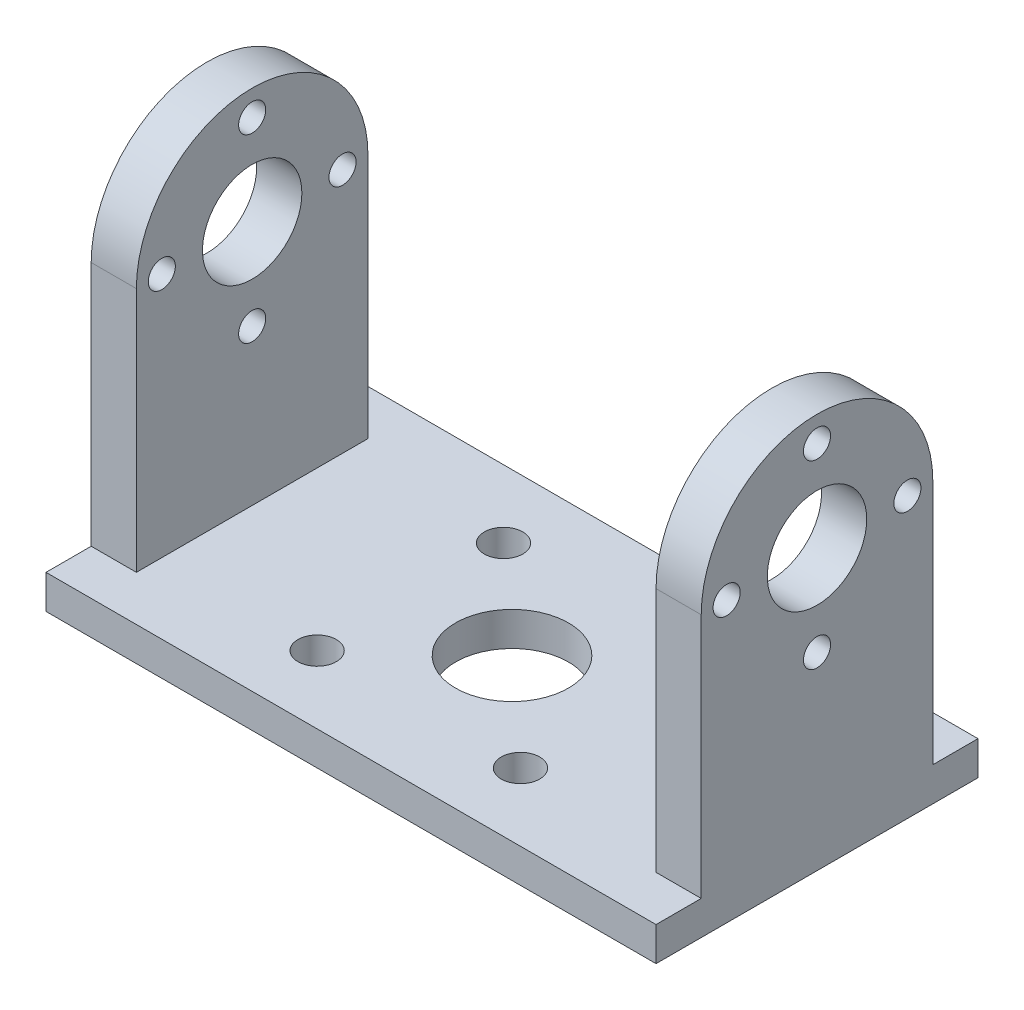
SolidWorks part; units mm, degrees
ref_plane "Front Plane" through (0, 0, 0) normal (0, 0, 1) x (1, 0, 0)
ref_plane "Top Plane" through (0, 0, 0) normal (0, 1, 0) x (1, 0, 0)
ref_plane "Right Plane" through (0, 0, 0) normal (1, 0, 0) x (0, 0, -1)
sketch "Sketch1" plane through (0, 0, 0) normal (0, 1, 0) x (1, 0, 0)
  line L0 (0, 0) -> (0, -7.6155) construction
  line L1 (-18, 14.25) -> (18, 14.25)
  line L2 (-18, 14.25) -> (-18, -14.25)
  line L3 (-18, -14.25) -> (18, -14.25)
  line L4 (18, 14.25) -> (18, -14.25)
  line L6 (-18, 14.25) -> (-27, 14.25)
  line L7 (-18, 14.25) -> (-18, -14.25)
  line L8 (-18, -14.25) -> (-27, -14.25)
  line L9 (-27, 14.25) -> (-27, -14.25)
  line L10 (18, 14.25) -> (27, 14.25)
  line L11 (18, 14.25) -> (18, -14.25)
  line L12 (18, -14.25) -> (27, -14.25)
  line L13 (27, 14.25) -> (27, -14.25)
  circle A0 centre (0, 0) radius 5
  circle A1 centre (-9, 8.25) radius 1.7
  circle A2 centre (-9, -8.25) radius 1.7
  circle A3 centre (9, -8.25) radius 1.7
  circle A4 centre (9, 8.25) radius 1.7
  point P0 (0, 0)
  dimension "D3" = 9
  dimension "D4" = 8.25
  dimension "D5" = 8.25
  dimension "D6" = 9
  dimension "D7" = 9
  dimension "D1" = 36
  dimension "D2" = 28.5
  dimension "D8" = 9
extrude "Boss-Extrude2" add sketch "Sketch1" along normal blind 3
sketch "Sketch2" plane through (0, 3, 0) normal (0, 1, 0) x (1, 0, 0)
  line L5 (27, 14.25) -> (27, -14.25) construction
  line L6 (27, 10.25) -> (23, 10.25)
  line L7 (27, 10.25) -> (27, -10.25)
  line L8 (27, -10.25) -> (23, -10.25)
  line L9 (23, 10.25) -> (23, -10.25)
  line L10 (27, 14.25) -> (-27, 14.25) construction
  dimension "D1" = 4
  dimension "D2" = 20.5
  dimension "D3" = 4
extrude "Boss-Extrude3" add sketch "Sketch2" along normal blind 21.75
sketch "Sketch4" plane through (27, 0, 0) normal (1, 0, 0) x (0, 0, -1)
  line L0 (-10.25, 24.75) -> (10.25, 24.75) construction
  circle A0 centre (0, 24.75) radius 10.25
  point P18 (0, 17.75)
extrude "Boss-Extrude4" add sketch "Sketch4" against normal blind 4
ref_plane "Plane1" through (0, 0, 0) normal (1, 0, 0) x (0, 0, -1)
mirror "Mirror1" about plane through (0, 0, 0) normal (1, 0, 0) of "Boss-Extrude3", "Boss-Extrude4"
sketch "Sketch6" plane through (27, 0, 0) normal (1, 0, 0) x (0, 0, -1)
  line L0 (-10.25, 24.75) -> (10.25, 24.75) construction
  line L1 (0, 35) -> (0, 14.5) construction
  circle A6 centre (0, 24.75) radius 4.4
  circle A7 centre (0, 24.75) radius 8
  circle A8 centre (0, 32.75) radius 1.2
  circle A9 centre (8, 24.75) radius 1.2
  circle A10 centre (0, 16.75) radius 1.2
  circle A11 centre (-8, 24.75) radius 1.2
  circle A12 centre (0, 24.75) radius 10.25
  point P21 (0, 24.75)
  dimension "D1" = 8.8
  dimension "D2" = 16
  dimension "D3" = 4
  dimension "D4" = 2.4
extrude "Cut-Extrude3" cut sketch "Sketch6" against normal blind 4 contours A6 | A7 A11 | A7 A11 | A7 A10 | A7 A10 | A7 A9 | A7 A9 | A7 A8 | A7 A8
mirror "Mirror3" about plane through (0, 0, 0) normal (1, 0, 0) of "Cut-Extrude3"
